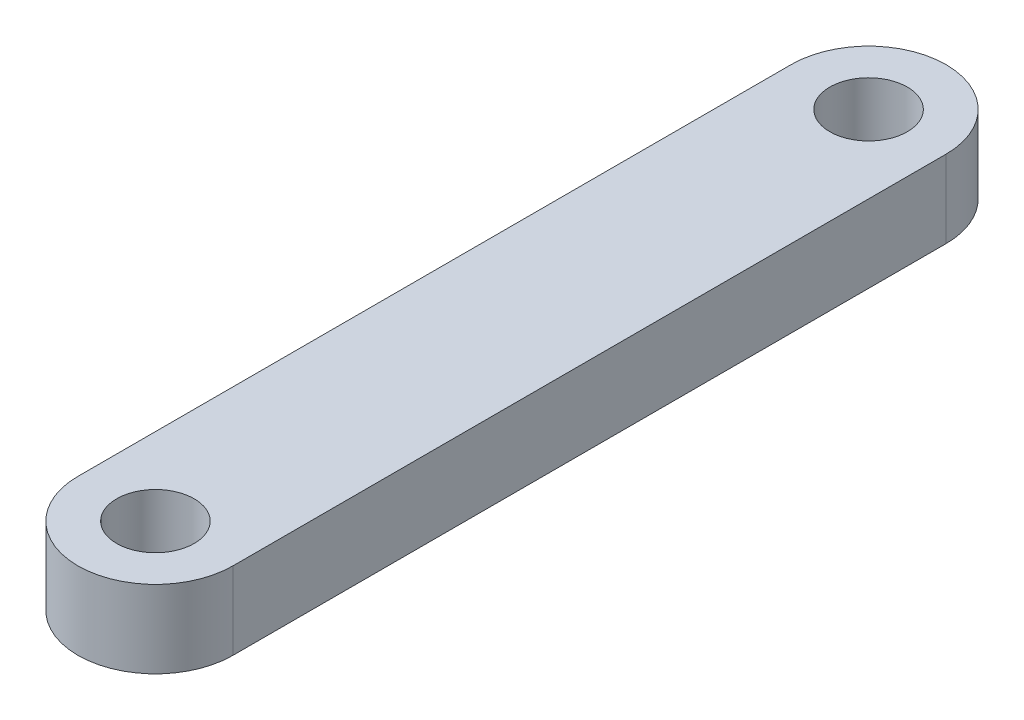
SolidWorks part; units mm, degrees
ref_plane "Front Plane" through (0, 0, 0) normal (0, 0, 1) x (1, 0, 0)
ref_plane "Top Plane" through (0, 0, 0) normal (0, 1, 0) x (1, 0, 0)
ref_plane "Right Plane" through (0, 0, 0) normal (1, 0, 0) x (0, 0, -1)
sketch "Sketch1" plane through (0, 0, 0) normal (0, 1, 0) x (1, 0, 0)
  line L0 (0, -29.21) -> (0, 29.21) construction
  line L1 (-6.35, -29.21) -> (-6.35, 29.21)
  line L2 (6.35, -29.21) -> (6.35, 29.21)
  arc A0 (-6.35, -29.21) -> (6.35, -29.21) centre (0, -29.21) ccw
  arc A1 (6.35, 29.21) -> (-6.35, 29.21) centre (0, 29.21) ccw
  circle A2 centre (0, 29.21) radius 3.175
  circle A3 centre (0, -29.21) radius 3.175
  point P2 (0, 0)
  dimension "D1" = 6.35
  dimension "D3" = 6.35
  dimension "D2" = 58.42
extrude "Boss-Extrude1" add sketch "Sketch1" along normal mid plane 6.35
